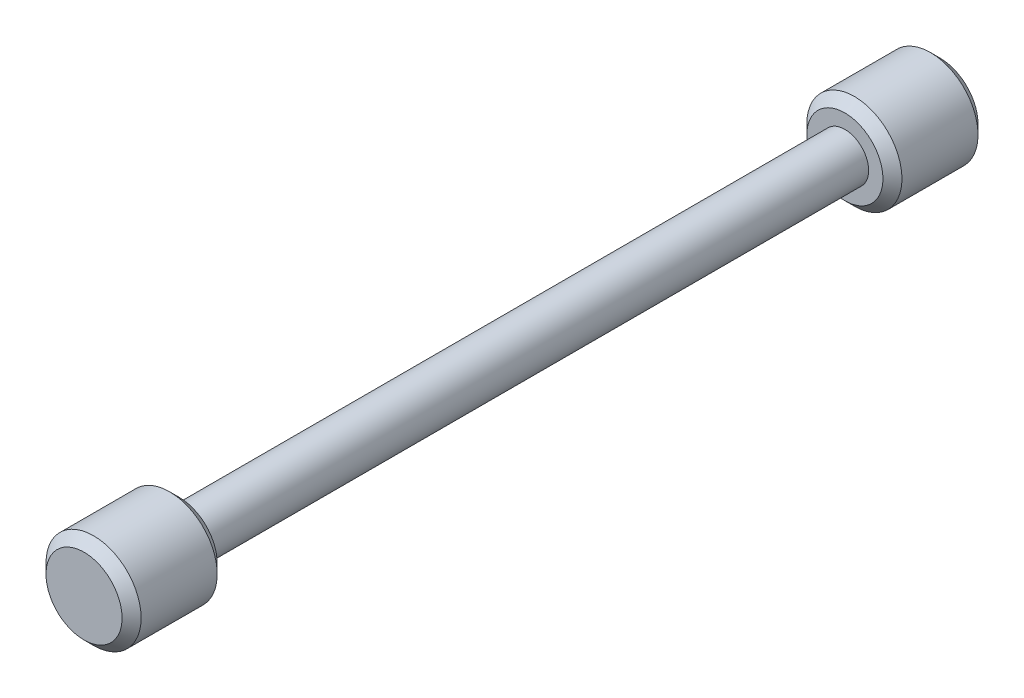
SolidWorks part; units mm, degrees
ref_plane "Front Plane" through (0, 0, 0) normal (0, 0, 1) x (1, 0, 0)
ref_plane "Top Plane" through (0, 0, 0) normal (0, 1, 0) x (1, 0, 0)
ref_plane "Right Plane" through (0, 0, 0) normal (1, 0, 0) x (0, 0, -1)
sketch "Sketch1" plane through (0, 0, 0) normal (1, 0, 0) x (0, 0, -1)
  line L0 (-44.45, 0) -> (44.45, 0)
  line L1 (44.45, 0) -> (44.45, 3.175)
  line L2 (44.45, 3.175) -> (57.15, 3.175)
  line L3 (0, 0) -> (0, 59.9825) construction
  line L4 (57.15, -3.175) -> (-54.589, -3.175) construction
  line L5 (-44.45, 3.175) -> (-57.15, 3.175)
  line L6 (-44.45, 0) -> (-44.45, 3.175)
  line L7 (-57.15, 3.175) -> (-57.15, -3.175)
  line L8 (-57.15, -3.175) -> (57.15, -3.175)
  line L9 (57.15, -3.175) -> (57.15, 3.175)
  dimension "D1" = 12.7
  dimension "D2" = 6.35
  dimension "D3" = 3.175
  dimension "D4" = 57.15
  dimension "D5" = 114.3
revolve "Revolve1" add sketch "Sketch1" angle 360 about L4
chamfer "Chamfer1" distance 1.27 angle 45 4 edges at (0, 3.175, -44.45) (0, 3.175, 44.45) (0, 3.175, -57.15) (0, 3.175, 57.15)
